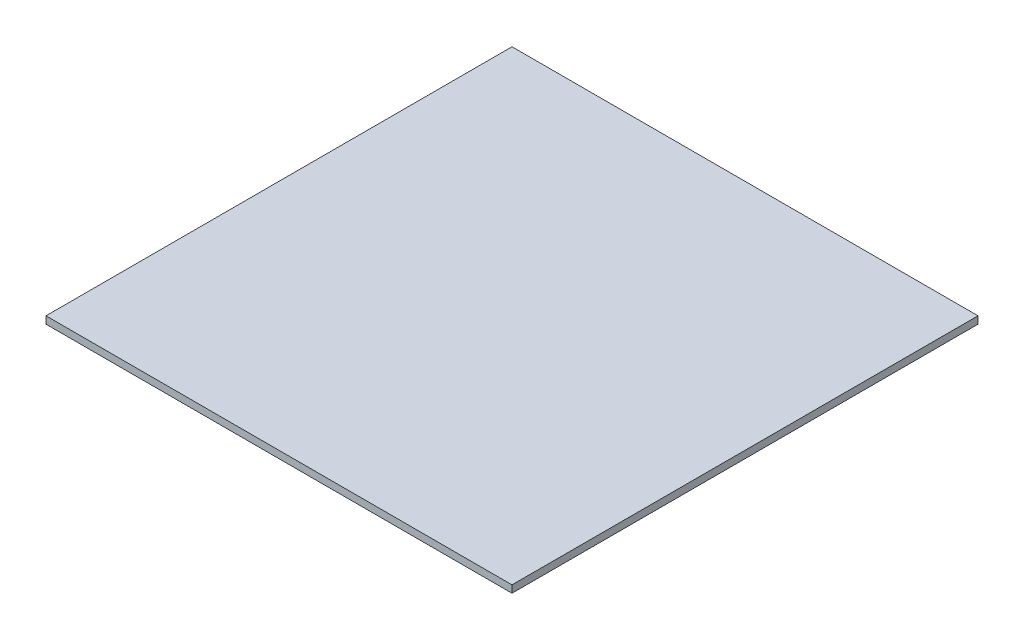
SolidWorks part; units mm, degrees
ref_plane "Front Plane" through (0, 0, 0) normal (0, 0, 1) x (1, 0, 0)
ref_plane "Top Plane" through (0, 0, 0) normal (0, 1, 0) x (1, 0, 0)
ref_plane "Right Plane" through (0, 0, 0) normal (1, 0, 0) x (0, 0, -1)
sketch "Sketch1" plane through (0, 0, 0) normal (0, 1, 0) x (1, 0, 0)
  line L0 (45.5876, 6.3811) -> (36.7056, 0)
  line L1 (0, 0) -> (203.2, 0)
  line L2 (0, 0) -> (0, 203.2)
  line L3 (0, 203.2) -> (203.2, 203.2)
  line L4 (203.2, 0) -> (203.2, 203.2)
  line L5 (15.6252, 166.8307) -> (183.6873, 166.8307) construction
  line L6 (43.4472, 91.3368) -> (42.5026, 97.6324)
  line L7 (43.7202, 92.6509) -> (42.1854, 101.9178)
  line L8 (44.0561, 94.1437) -> (42.0151, 104.5231)
  line L9 (44.4386, 95.7004) -> (41.8364, 107.3821)
  line L10 (44.7499, 96.8683) -> (41.6422, 110.461)
  line L11 (45.1559, 98.2748) -> (41.4486, 113.3273)
  line L12 (45.576, 99.6074) -> (41.2929, 115.4184)
  line L13 (46.0018, 100.846) -> (41.0891, 117.8593)
  line L14 (46.4271, 101.9828) -> (40.9495, 119.3524)
  line L15 (46.701, 102.6669) -> (40.8447, 120.3876)
  line L16 (47.0086, 103.3939) -> (40.7505, 121.2641)
  line L17 (47.3159, 104.0795) -> (40.6419, 122.214)
  line L18 (47.5887, 104.6562) -> (41.0713, 121.8791)
  line L19 (47.9504, 105.3773) -> (41.5816, 121.4809)
  line L20 (48.2716, 105.9791) -> (42.2373, 120.9688)
  line L21 (48.6154, 106.5853) -> (43.0399, 120.3417)
  line L22 (48.99, 107.204) -> (43.6355, 119.8759)
  line L23 (49.2717, 107.6422) -> (44.3559, 119.3121)
  line L24 (49.6602, 108.2109) -> (45.0871, 118.7392)
  line L25 (50.0721, 108.771) -> (45.9493, 118.0628)
  line L26 (50.5059, 109.3164) -> (46.6667, 117.4993)
  line L27 (50.8603, 109.7299) -> (47.578, 116.7823)
  line L28 (48.6333, 115.9503) -> (51.3273, 110.2338)
  line L29 (51.7467, 110.6484) -> (49.3156, 115.4111)
  line L30 (52.203, 111.0615) -> (50.1506, 114.7498)
  line L31 (52.6555, 111.434) -> (51.1461, 113.9592)
  line L32 (53.0516, 111.7314) -> (52.3423, 113.0053)
  line L33 (53.3487, 111.9377) -> (53.1663, 112.3454)
  line L34 (159.3258, 89.6209) -> (165.8977, 102.1692)
  line L35 (159.5487, 91.1131) -> (167.1112, 105.3282)
  line L36 (159.7729, 92.883) -> (167.5256, 106.4623)
  line L37 (159.9209, 94.3165) -> (168.0059, 107.8155)
  line L38 (160.0293, 95.6352) -> (168.306, 108.6838)
  line L39 (160.0952, 96.6748) -> (168.4549, 109.1214)
  line L40 (160.1354, 97.5142) -> (168.7088, 109.8787)
  line L41 (160.1701, 98.6209) -> (168.8989, 110.4549)
  line L42 (160.1833, 99.8454) -> (169.0829, 111.0207)
  line L43 (160.1752, 100.7562) -> (169.2777, 111.6283)
  line L44 (160.1508, 101.686) -> (169.4776, 112.2619)
  line L45 (160.1111, 102.5827) -> (169.7425, 113.1172)
  line L46 (160.0562, 103.4624) -> (170.0164, 114.0216)
  line L47 (159.9634, 104.5762) -> (170.2718, 114.8847)
  line L48 (159.86, 105.5493) -> (170.4978, 115.6646)
  line L49 (159.748, 106.4288) -> (170.7049, 116.3939)
  line L50 (159.591, 107.4742) -> (170.8524, 116.9222)
  line L51 (159.4988, 108.0172) -> (171.1076, 117.8546)
  line L52 (159.405, 108.5296) -> (171.4302, 119.068)
  line L53 (159.2885, 109.1198) -> (171.7178, 120.186)
  line L54 (159.19, 109.5853) -> (171.9298, 121.0329)
  line L55 (159.0944, 110.0132) -> (172.1325, 121.8628)
  line L56 (158.9429, 110.6484) -> (168.4549, 119.6355)
  line L57 (158.7252, 111.4874) -> (166.0694, 118.1139)
  line L58 (158.6171, 111.8768) -> (164.2716, 116.9243)
  line L59 (55.5599, 64.695) -> (44.0561, 94.1437)
  line L60 (58.1743, 68.4963) -> (45.576, 99.6074)
  line L61 (61.3484, 72.2314) -> (47.5887, 104.6562)
  line L62 (68.5448, 78.1725) -> (50.5059, 109.3164)
  line L63 (70.9077, 79.5512) -> (52.203, 111.0615)
  line L64 (53.5276, 112.0552) -> (74.8649, 81.3725)
  line L65 (43.4472, 91.3368) -> (54.3406, 62.6398)
  line L66 (48.99, 107.204) -> (65.0134, 75.6263)
  line L67 (145.9127, 70.5897) -> (159.5487, 91.1131)
  line L68 (144.3017, 72.6355) -> (160.0952, 96.6748)
  line L69 (141.5235, 75.6263) -> (160.1752, 100.7562)
  line L70 (138.6575, 78.1725) -> (159.86, 105.5493)
  line L71 (159.19, 109.5853) -> (135.5441, 80.4713)
  line L72 (158.7252, 111.4874) -> (132.9803, 82.0752)
  line L88 (65.3688, 54.5462) -> (65.3688, 50.5785)
  line L89 (65.3688, 59.4685) -> (65.3688, 55.8682)
  line L90 (68.5438, 47.4035) -> (87.5938, 47.4035)
  line L91 (90.7688, 59.4685) -> (90.7688, 55.6585)
  line L92 (68.5438, 62.6435) -> (87.5938, 62.6435)
  line L93 (90.7688, 54.3885) -> (108.8676, 54.3885)
  line L94 (112.0426, 62.6435) -> (131.0926, 62.6435)
  line L95 (134.2676, 59.4685) -> (134.2676, 55.8245)
  line L96 (112.0426, 47.4035) -> (131.0926, 47.4035)
  line L97 (108.8676, 59.4685) -> (108.8676, 55.6585)
  line L98 (134.2676, 54.5201) -> (152.7506, 58.8503)
  line L99 (65.3688, 54.5462) -> (51.5284, 58.5488)
  line L100 (66.6388, 59.4685) -> (66.6388, 50.5785)
  line L101 (68.5438, 48.6735) -> (87.5938, 48.6735)
  line L102 (89.4988, 59.4685) -> (89.4988, 50.5785)
  line L103 (68.5438, 61.3735) -> (87.5938, 61.3735)
  line L104 (90.7688, 55.6585) -> (108.8676, 55.6585)
  line L105 (112.0426, 61.3735) -> (131.0926, 61.3735)
  line L106 (132.9976, 59.4685) -> (132.9976, 50.5785)
  line L107 (112.0426, 48.6735) -> (131.0926, 48.6735)
  line L108 (110.1376, 59.4685) -> (110.1376, 50.5785)
  line L109 (133.4878, 55.6418) -> (133.6326, 55.6757)
  line L110 (90.7688, 54.3885) -> (90.7688, 50.5785)
  line L112 (65.3688, 55.8682) -> (51.8812, 59.7688)
  line L114 (134.2676, 55.8245) -> (152.4609, 60.0868)
  line L116 (108.8676, 54.3885) -> (108.8676, 50.5785)
  line L117 (134.2676, 54.5201) -> (134.2676, 50.5785)
  circle A0 centre (77.4338, 55.6585) radius 4.5299
  circle A1 centre (120.9326, 55.6585) radius 4.5299
  circle A2 centre (76.1664, 57.4105) radius 1.205
  circle A3 centre (119.6626, 56.9285) radius 1.205
  circle A4 centre (55.3805, 28.853) radius 7.62
  circle A5 centre (146.9804, 28.853) radius 7.62
  arc A15 (65.3688, 50.5785) -> (68.5438, 47.4035) centre (68.5438, 50.5785) ccw
  arc A16 (87.5938, 47.4035) -> (90.7688, 50.5785) centre (87.5938, 50.5785) ccw
  arc A17 (87.5938, 62.6435) -> (90.7688, 59.4685) centre (87.5938, 59.4685) cw
  arc A18 (68.5438, 62.6435) -> (65.3688, 59.4685) centre (68.5438, 59.4685) ccw
  arc A19 (131.0926, 62.6435) -> (134.2676, 59.4685) centre (131.0926, 59.4685) cw
  arc A20 (131.0926, 47.4035) -> (134.2676, 50.5785) centre (131.0926, 50.5785) ccw
  arc A21 (108.8676, 50.5785) -> (112.0426, 47.4035) centre (112.0426, 50.5785) ccw
  arc A22 (112.0426, 62.6435) -> (108.8676, 59.4685) centre (112.0426, 59.4685) ccw
  arc A23 (66.6388, 50.5785) -> (68.5438, 48.6735) centre (68.5438, 50.5785) ccw
  arc A24 (87.5938, 48.6735) -> (89.4988, 50.5785) centre (87.5938, 50.5785) ccw
  arc A25 (87.5938, 61.3735) -> (89.4988, 59.4685) centre (87.5938, 59.4685) cw
  arc A26 (68.5438, 61.3735) -> (66.6388, 59.4685) centre (68.5438, 59.4685) ccw
  arc A27 (131.0926, 61.3735) -> (132.9976, 59.4685) centre (131.0926, 59.4685) cw
  arc A28 (131.0926, 48.6735) -> (132.9976, 50.5785) centre (131.0926, 50.5785) ccw
  arc A29 (110.1376, 50.5785) -> (112.0426, 48.6735) centre (112.0426, 50.5785) ccw
  arc A30 (112.0426, 61.3735) -> (110.1376, 59.4685) centre (112.0426, 59.4685) ccw
  ellipse E0 centre (92.8656, 39.5872) end of major axis (96.6756, 39.5872) minor radius 2.54
  ellipse E1 centre (96.6756, 20.5372) end of major axis (89.0556, 20.5372) minor radius 6.35
  spline S0 degree 2 poles (54.0799, 62.1733) (40.2888, 46.9486) (45.5876, 6.3811) knots 0 0 0 1 1 1
  spline S1 degree 3 poles (40.6419, 122.214) (43.0993, 101.3847) (40.8684, 76.2884) (54.0799, 62.1733) knots 0 0 0 0 1 1 1 1
  spline S2 degree 3 poles (40.6419, 122.214) (72.6787, 97.2268) (68.3789, 99.6212) (77.7814, 82.3786) knots 0 0 0 0 1 1 1 1
  spline S3 degree 2 poles (77.7814, 82.3786) (106.6411, 91.1069) (130.7827, 83.2779) knots 0 0 0 1 1 1
  spline S4 degree 2 poles (130.7827, 83.2779) (144.9925, 105.9262) (172.1325, 121.8628) knots 0 0 0 1 1 1
  spline S5 degree 2 poles (172.1325, 121.8628) (164.9738, 92.1954) (146.9547, 69.1107) knots 0 0 0 1 1 1
  spline S6 degree 3 poles (146.9547, 69.1107) (167.679, 39.6793) (150.8507, 18.0622) (154.4315, 0) knots 0 0 0 0 1 1 1 1
  spline S7 degree 2 poles (53.5276, 112.0552) (46.508, 107.5418) (43.2467, 90.3071) knots 0 0 0 1 1 1
  spline S8 degree 2 poles (158.3651, 112.7269) (161.6965, 101.973) (158.9238, 87.317) knots 0 0 0 1 1 1
  spline S9 degree 2 poles (44.5056, 82.6463) (49.6225, 99.7833) (56.5813, 109.5771) knots 0 0 0 1 1 1
  spline S10 degree 2 poles (46.7059, 74.7089) (51.369, 93.9159) (61.1576, 105.7253) knots 0 0 0 1 1 1
  spline S11 degree 2 poles (49.1189, 69.1964) (55.0075, 88.4934) (65.6507, 101.5729) knots 0 0 0 1 1 1
  spline S12 degree 2 poles (51.7048, 65.0458) (58.5714, 84.3065) (70.8218, 95.2471) knots 0 0 0 1 1 1
  spline S13 degree 2 poles (54.0799, 62.1733) (62.7487, 77.8543) (77.7814, 82.3786) knots 0 0 0 1 1 1
  spline S14 degree 2 poles (146.9547, 69.1107) (140.9417, 78.0488) (130.7827, 83.2779) knots 0 0 0 1 1 1
  spline S15 degree 2 poles (149.1837, 72.0478) (143.3773, 83.1914) (135.1131, 89.6209) knots 0 0 0 1 1 1
  spline S16 degree 2 poles (151.7341, 75.6263) (148.7328, 88.4332) (140.8353, 96.6748) knots 0 0 0 1 1 1
  spline S17 degree 2 poles (154.4315, 79.7029) (152.8402, 92.4909) (145.5619, 101.682) knots 0 0 0 1 1 1
  spline S18 degree 2 poles (156.6257, 83.2779) (156.3754, 97.1726) (151.7341, 107.3943) knots 0 0 0 1 1 1
  spline S19 degree 2 poles (52.986, 63.4084) (63.877, 82.9517) (74.4245, 88.7425) knots 0 0 0 1 1 1
  spline S20 degree 2 poles (74.8649, 81.3725) (104.0447, 85.7155) (132.9803, 82.0752) knots 0 0 0 1 1 1
  spline S21 degree 2 poles (63.9278, 74.7089) (103.3649, 80.9304) (141.5235, 75.6263) knots 0 0 0 1 1 1
  spline S22 degree 2 poles (58.1743, 68.4963) (104.2209, 74.7271) (145.9127, 70.5897) knots 0 0 0 1 1 1
  spline S23 degree 2 poles (54.3406, 62.6398) (105.6198, 67.9772) (150.5985, 63.3583) knots 0 0 0 1 1 1
  spline S24 degree 3 poles (49.9108, 56.2055) (52.5561, 56.3966) (55.1884, 56.5724) (57.8078, 56.7328) knots 0 0 0 0 0.070661 0.070661 0.070661 0.070661
  spline S25 degree 1 poles (46.3974, 47.1022) (156.8689, 45.729) knots 0 0 1 1
  spline S26 degree 3 poles (44.7419, 38.2555) (79.3727, 35.154) (112.8415, 34.4853) (145.1481, 36.2494) knots 0 0 0 0 0.886438 0.886438 0.886438 0.886438
  spline S27 degree 3 poles (44.1168, 26.8872) (45.434, 26.8275) (46.7506, 26.7698) (48.0668, 26.7142) knots 0 0 0 0 0.034688 0.034688 0.034688 0.034688
  spline S28 degree 3 poles (44.4323, 17.9087) (59.9159, 17.0395) (75.3745, 16.5653) (90.8079, 16.4859) knots 0 0 0 0 0.417175 0.417175 0.417175 0.417175
  spline S29 degree 2 poles (45.238, 9.2077) (100.5735, 5.859) (153.9978, 8.3142) knots 0 0 0 1 1 1
  spline S30 degree 2 poles (41.1466, 3.1905) (98.0432, 0.4816) (154.0023, 3.1905) knots 0 0 0 1 1 1
  spline S31 degree 2 poles (45.5876, 6.3811) (44.3704, 1.9192) (44.4323, 0) knots 0 0 0 1 1 1
  spline S32 degree 2 poles (44.7419, 38.2555) (45.5836, 15.9085) (49.9108, 0) knots 0 0 0 1 1 1
  spline S33 degree 2 poles (49.9108, 56.2055) (50.2312, 45.6942) (51.42, 35.3629) knots 0 0 0 0.36526 0.36526 0.36526
  spline S34 degree 2 poles (58.1743, 68.4963) (58.1093, 63.1972) (58.2358, 57.9311) knots 0 0 0 0.151558 0.151558 0.151558
  spline S35 degree 2 poles (68.5448, 78.1725) (68.2483, 70.3713) (68.3577, 62.6381) knots 0 0 0 0.19513 0.19513 0.19513
  spline S36 degree 2 poles (77.7814, 82.3786) (77.5335, 72.458) (77.8905, 62.6435) knots 0 0 0 0.235384 0.235384 0.235384
  spline S37 degree 2 poles (104.2956, 86.9398) (105.1223, 71.3016) (105.6982, 55.6585) knots 0 0 0 0.359904 0.359904 0.359904
  spline S38 degree 2 poles (115.4188, 86.5347) (116.6911, 74.5848) (117.4254, 62.6435) knots 0 0 0 0.275827 0.275827 0.275827
  spline S39 degree 2 poles (125.6599, 84.7397) (126.6025, 73.6811) (127.0548, 62.6435) knots 0 0 0 0.260048 0.260048 0.260048
  spline S40 degree 2 poles (142.3048, 74.8442) (142.6994, 66.3214) (142.7889, 57.8208) knots 0 0 0 0.226436 0.226436 0.226436
  spline S41 degree 3 poles (78.5108, 51.2586) (78.5735, 50.3963) (78.6397, 49.5346) (78.7095, 48.6735) knots 0.372338 0.372338 0.372338 0.372338 0.403556 0.403556 0.403556 0.403556
  spline S42 degree 2 poles (148.4788, 66.8575) (148.5964, 63.024) (148.6539, 59.1949) knots 0 0 0 0.1141 0.1141 0.1141
  spline S43 degree 2 poles (154.4315, 55.0931) (154.3813, 43.7134) (153.7268, 32.3956) knots 0 0 0 0.410369 0.410369 0.410369
  spline S44 degree 2 poles (90.5858, 85.4783) (90.5513, 70.5273) (91.2743, 55.6585) knots 0 0 0 0.347049 0.347049 0.347049
  spline S45 degree 2 poles (135.5441, 80.4713) (136.2703, 68.364) (136.3338, 56.3085) knots 0 0 0 0.298752 0.298752 0.298752
  spline S46 degree 3 poles (81.44, 57.7727) (84.1409, 57.8435) (86.8272, 57.897) (89.4988, 57.9331) knots 0.286426 0.286426 0.286426 0.286426 0.361557 0.361557 0.361557 0.361557
  spline S47 degree 3 poles (125.1373, 57.344) (127.7732, 57.2171) (130.3933, 57.0714) (132.9976, 56.907) knots 0.704207 0.704207 0.704207 0.704207 0.78224 0.78224 0.78224 0.78224
  spline S48 degree 3 poles (117.9632, 52.2377) (118.0129, 51.0496) (118.0587, 49.8615) (118.1004, 48.6735) knots 0.396025 0.396025 0.396025 0.396025 0.437204 0.437204 0.437204 0.437204
  spline S49 degree 3 poles (61.1114, 23.831) (62.279, 15.828) (63.7921, 7.8843) (65.6507, 0) knots 0.647313 0.647313 0.647313 0.647313 1 1 1 1
  spline S50 degree 3 poles (53.4221, 21.4889) (54.6795, 14.2582) (56.2635, 7.0952) (58.1743, 0) knots 0.611969 0.611969 0.611969 0.611969 1 1 1 1
  spline S51 degree 3 poles (62.5187, 26.1864) (72.4152, 25.8817) (82.2816, 25.6949) (92.1177, 25.626) knots 0.161844 0.161844 0.161844 0.161844 0.423457 0.423457 0.423457 0.423457
  spline S52 degree 3 poles (141.8825, 23.1894) (141.3941, 15.4456) (140.7138, 7.7158) (139.8417, 0) knots 0.688924 0.688924 0.688924 0.688924 1 1 1 1
  spline S53 degree 2 poles (154.3125, 26.7784) (155.5106, 26.8316) (156.7081, 26.8872) knots 0.978476 0.978476 0.978476 1 1 1
  spline S54 degree 3 poles (147.7379, 21.2707) (147.2868, 14.169) (146.6783, 7.0787) (145.9127, 0) knots 0.680749 0.680749 0.680749 0.680749 1 1 1 1
  spline S55 degree 3 poles (153.1914, 24.4385) (152.5642, 16.268) (151.6999, 8.1219) (150.5985, 0) knots 0.554767 0.554767 0.554767 0.554767 1 1 1 1
  spline S56 degree 2 poles (147.9625, 36.4094) (152.752, 36.6925) (157.5074, 37.0472) knots 0.912205 0.912205 0.912205 1 1 1
  spline S57 degree 3 poles (101.2816, 25.5958) (114.1828, 25.6015) (127.0317, 25.8106) (139.8285, 26.2234) knots 0.50478 0.50478 0.50478 0.50478 0.84857 0.84857 0.84857 0.84857
  spline S58 degree 2 poles (102.5591, 16.5018) (129.0019, 16.7096) (155.3463, 18.4657) knots 0.523099 0.523099 0.523099 1 1 1
  spline S59 degree 3 poles (94.7583, 14.3915) (95.3372, 9.5878) (95.9763, 4.7906) (96.6756, 0) knots 0.830512 0.830512 0.830512 0.830512 1 1 1 1
  spline S60 degree 3 poles (92.4773, 37.0604) (92.7678, 33.4666) (93.0916, 29.8764) (93.4489, 26.2898) knots 0.564473 0.564473 0.564473 0.564473 0.690735 0.690735 0.690735 0.690735
  spline S61 degree 3 poles (61.6096, 56.9554) (63.0784, 57.0373) (64.5432, 57.1145) (66.0038, 57.1867) knots 0.10493 0.10493 0.10493 0.10493 0.144745 0.144745 0.144745 0.144745
  spline S62 degree 3 poles (58.2709, 56.5989) (58.4772, 49.3973) (58.9523, 42.242) (59.6964, 35.1329) knots 0.170735 0.170735 0.170735 0.170735 0.481866 0.481866 0.481866 0.481866
  spline S63 degree 3 poles (66.6388, 57.2178) (68.8684, 57.326) (71.0884, 57.4228) (73.2988, 57.5083) knots 0.150517 0.150517 0.150517 0.150517 0.211345 0.211345 0.211345 0.211345
  spline S64 degree 3 poles (68.3784, 61.3663) (68.4569, 57.12) (68.6273, 52.8891) (68.8896, 48.6735) knots 0.21118 0.21118 0.21118 0.21118 0.372018 0.372018 0.372018 0.372018
  spline S65 degree 3 poles (68.9714, 47.4035) (70.0395, 31.3794) (72.4379, 15.5782) (76.1664, 0) knots 0.388175 0.388175 0.388175 0.388175 1 1 1 1
  spline S66 degree 3 poles (78.8151, 47.4035) (80.179, 31.3869) (82.7721, 15.5857) (86.5942, 0) knots 0.418909 0.418909 0.418909 0.418909 1 1 1 1
  spline S67 degree 3 poles (90.7688, 57.949) (96.8786, 58.0191) (102.9116, 57.9982) (108.8676, 57.8861) knots 0.373473 0.373473 0.373473 0.373473 0.545596 0.545596 0.545596 0.545596
  spline S68 degree 3 poles (77.9393, 61.3735) (77.9557, 60.9669) (77.9729, 60.5604) (77.9909, 60.154) knots 0.250618 0.250618 0.250618 0.250618 0.265258 0.265258 0.265258 0.265258
  spline S69 degree 3 poles (91.3374, 54.3885) (91.5462, 50.2792) (91.7984, 46.1745) (92.094, 42.0745) knots 0.361872 0.361872 0.361872 0.361872 0.50578 0.50578 0.50578 0.50578
  spline S70 degree 3 poles (105.7445, 54.3885) (106.3999, 36.2639) (106.8028, 18.1344) (106.953, 0) knots 0.374513 0.374513 0.374513 0.374513 1 1 1 1
  spline S71 degree 3 poles (134.2676, 56.8253) (135.371, 56.7529) (136.4716, 56.6771) (137.5693, 56.598) knots 0.794936 0.794936 0.794936 0.794936 0.828062 0.828062 0.828062 0.828062
  spline S72 degree 3 poles (110.1376, 57.8607) (112.3956, 57.8132) (114.6425, 57.7526) (116.8783, 57.6788) knots 0.557841 0.557841 0.557841 0.557841 0.623213 0.623213 0.623213 0.623213
  spline S73 degree 3 poles (117.5019, 61.3735) (117.5531, 60.5086) (117.6021, 59.6438) (117.6489, 58.7789) knots 0.290495 0.290495 0.290495 0.290495 0.320463 0.320463 0.320463 0.320463
  spline S74 degree 3 poles (127.1052, 61.3735) (127.268, 57.1379) (127.3767, 52.9045) (127.4311, 48.6735) knots 0.27501 0.27501 0.27501 0.27501 0.424716 0.424716 0.424716 0.424716
  spline S75 degree 3 poles (127.4458, 47.4035) (127.6091, 31.5698) (127.0138, 15.7687) (125.6599, 0) knots 0.439695 0.439695 0.439695 0.439695 1 1 1 1
  spline S76 degree 3 poles (118.1435, 47.4035) (118.6614, 31.591) (118.4711, 15.7899) (117.5727, 0) knots 0.451878 0.451878 0.451878 0.451878 1 1 1 1
  spline S77 degree 3 poles (136.3387, 55.0053) (136.381, 36.5793) (135.2615, 18.2442) (132.9803, 0) knots 0.314902 0.314902 0.314902 0.314902 1 1 1 1
  spline S78 degree 2 poles (141.7694, 56.2776) (148.1658, 55.7628) (154.4315, 55.0931) knots 0.870454 0.870454 0.870454 1 1 1
  spline S79 degree 3 poles (142.8008, 56.5192) (142.8568, 49.3345) (142.7493, 42.1617) (142.4784, 35.0008) knots 0.243774 0.243774 0.243774 0.243774 0.530909 0.530909 0.530909 0.530909
  spline S80 degree 3 poles (148.6716, 57.8947) (148.7604, 50.6942) (148.6892, 43.5054) (148.4582, 36.3283) knots 0.133473 0.133473 0.133473 0.133473 0.455375 0.455375 0.455375 0.455375
  text T0 "Touretzky: Don't use AutoCAD for class\r\nStudent: Uses AutoCAD for each project\r\nTouretzky:" font "Century Gothic" height 6.35
  dimension "D1" = 203.2
  dimension "D2" = 203.2
extrude "Boss-Extrude1" add sketch "Sketch1" along normal blind 3.175 contours L2 L3 L4 L1
